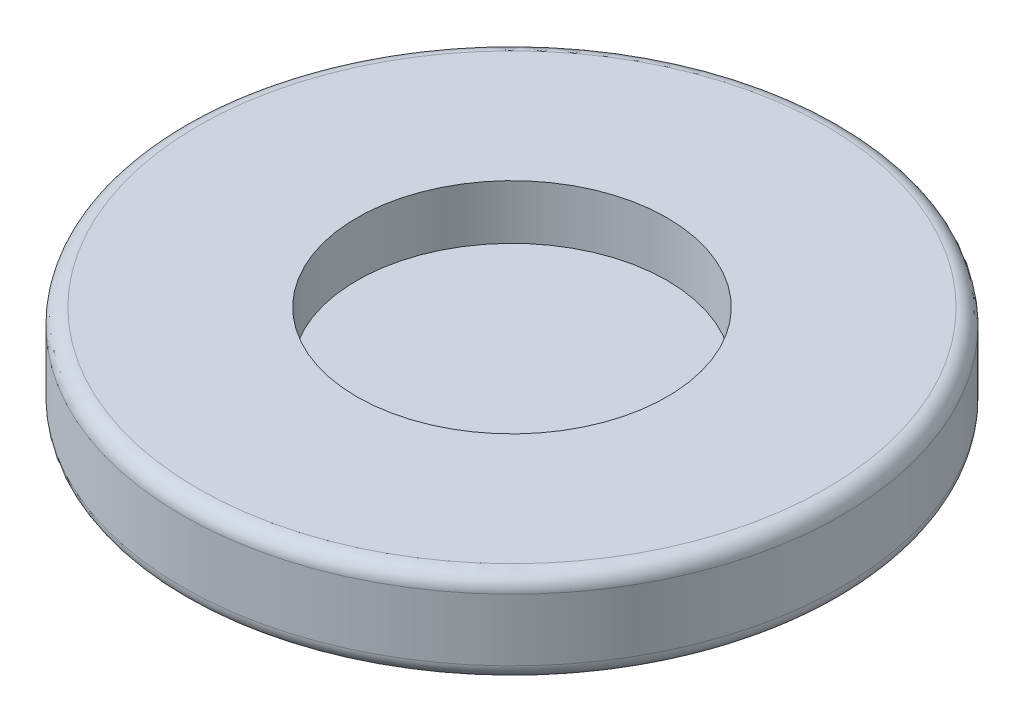
SolidWorks part; units mm, degrees
ref_plane "Front Plane" through (0, 0, 0) normal (0, 0, 1) x (1, 0, 0)
ref_plane "Top Plane" through (0, 0, 0) normal (0, 1, 0) x (1, 0, 0)
ref_plane "Right Plane" through (0, 0, 0) normal (1, 0, 0) x (0, 0, -1)
sketch "Sketch1" plane through (0, 0, 0) normal (0, 1, 0) x (1, 0, 0)
  circle A0 centre (0, 0) radius 42.5
  dimension "D1" = 85
extrude "Boss-Extrude1" add sketch "Sketch1" along normal blind 12
sketch "Sketch2" plane through (0, 12, 0) normal (0, 1, 0) x (1, 0, 0)
  circle A0 centre (0, 0) radius 20
  dimension "D1" = 40
extrude "Cut-Extrude1" cut sketch "Sketch2" against normal blind 7
fillet "Fillet1" radius 2 1 edges at (0, 12, 42.5)
fillet "Fillet2" radius 2 1 edges at (0, 0, 42.5)
